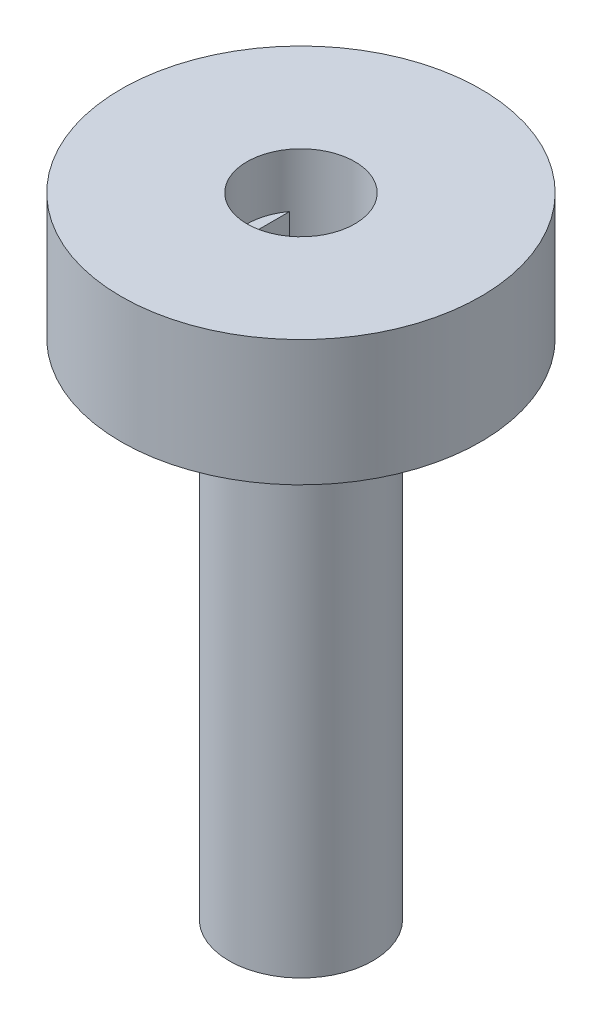
SolidWorks part; units mm, degrees
ref_plane "Plan de face" through (0, 0, 0) normal (0, 0, 1) x (1, 0, 0)
ref_plane "Plan de dessus" through (0, 0, 0) normal (0, 1, 0) x (1, 0, 0)
ref_plane "Plan de droite" through (0, 0, 0) normal (1, 0, 0) x (0, 0, -1)
sketch "Esquisse1" plane through (0, 0, 0) normal (0, 1, 0) x (1, 0, 0)
  circle A0 centre (0, 0) radius 4
  dimension "D1" = 8
extrude "Boss.-Extru.1" add sketch "Esquisse1" against normal blind 35
sketch "Esquisse2" plane through (0, 0, 0) normal (0, 1, 0) x (1, 0, 0)
  circle A0 centre (0, 0) radius 3
  dimension "D1" = 6
extrude "Enlèv. mat.-Extru.1" cut sketch "Esquisse2" against normal blind 13
sketch "Esquisse4" plane through (0, -13, 0) normal (0, 1, 0) x (1, 0, 0)
  line L0 (0, 0) -> (-2.41, 0)
  line L1 (-2.41, 0) -> (-2.41, -1.7866)
  line L2 (-2.41, -1.7866) -> (-3.1305, -1.7866)
  line L3 (-2.41, 0) -> (-2.41, 1.7866)
  line L5 (-2.41, 1.7866) -> (-3.1305, 1.7866)
  line L6 (-2.41, 1.7866) -> (-2.41, -1.7866)
  line L7 (-2.41, -1.7866) -> (-3.1305, -1.7866)
  line L8 (-3.1305, 1.7866) -> (-3.1305, -1.7866)
  circle A0 centre (0, 0) radius 3 construction
  circle M2 centre (0, 0) radius 3
  dimension "D1" = 2.41
extrude "Boss.-Extru.2" add sketch "Esquisse4" along normal blind 10 contours L1 L3 M2
sketch "Esquisse5" plane through (0, 0, 0) normal (0, 1, 0) x (1, 0, 0)
  circle A0 centre (0, 0) radius 10
  circle A1 centre (0, 0) radius 4
  dimension "D1" = 20
extrude "Boss.-Extru.3" add sketch "Esquisse5" against normal blind 7
